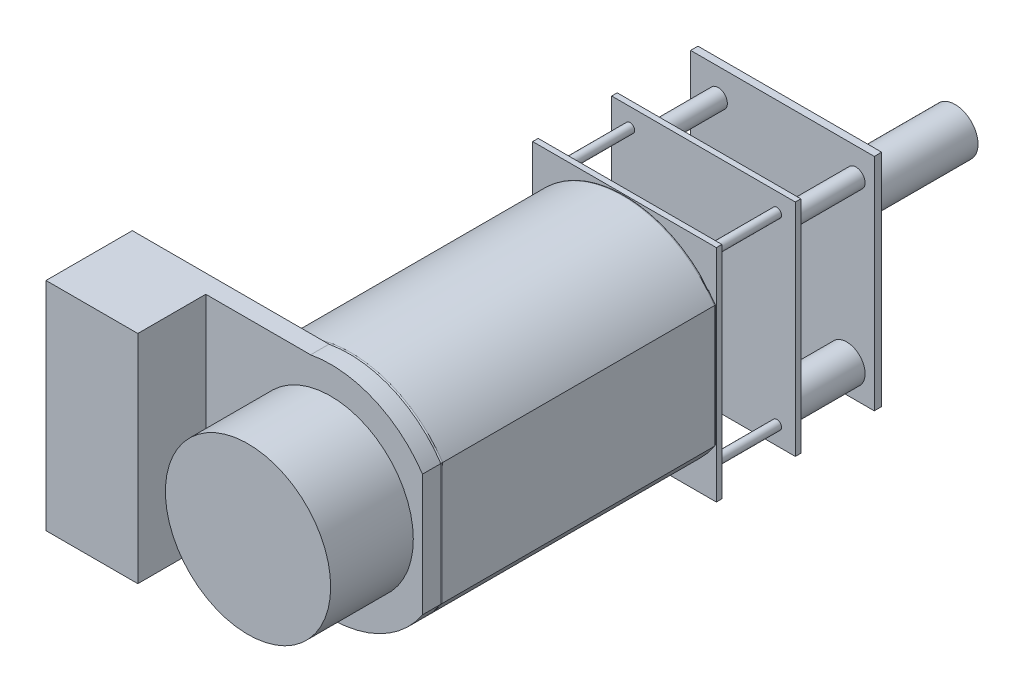
SolidWorks part; units mm, degrees
ref_plane "Front Plane" through (0, 0, 0) normal (0, 0, 1) x (1, 0, 0)
ref_plane "Top Plane" through (0, 0, 0) normal (0, 1, 0) x (1, 0, 0)
ref_plane "Right Plane" through (0, 0, 0) normal (1, 0, 0) x (0, 0, -1)
sketch "Sketch1" plane through (0, 0, 0) normal (0, 0, 1) x (1, 0, 0)
  line L2 (-5, -3.3166) -> (-5, 3.3166)
  line L4 (5, -3.3166) -> (5, 3.3166)
  line L5 (-3.8411, -4.6093) -> (3.8411, 4.6093) construction
  line L6 (-3.8411, 4.6093) -> (3.8411, -4.6093) construction
  arc A0 (-5, -3.3166) -> (5, -3.3166) centre (0, 0) ccw
  arc A1 (5, 3.3166) -> (-5, 3.3166) centre (0, 0) ccw
  point P0 (0, 0)
  dimension "D3" = 12
  dimension "D1" = 5
  dimension "D2" = 3.8411
extrude "Boss-Extrude1" add sketch "Sketch1" along normal blind 15
fillet "Fillet1" radius 0.1 8 edges at (0, -6, 15) (-5, 0, 15) (0, 6, 15) (5, 0, 15) (0, -6, 0) (5, 0, 0) (-5, 0, 0) (0, 6, 0)
sketch "Sketch2" plane through (0, 0, 15) normal (0, 0, 1) x (1, 0, 0)
  circle A0 centre (0, 0) radius 2.5
  dimension "D1" = 5
extrude "Boss-Extrude2" add sketch "Sketch2" along normal blind 1
sketch "Sketch3" plane through (0, 0, 16) normal (0, 0, 1) x (1, 0, 0)
  circle A0 centre (0, 0) radius 1.25
  dimension "D1" = 2.5
extrude "Boss-Extrude3" add sketch "Sketch3" along normal blind 0.1
sketch "Sketch4" plane through (0, 0, 0) normal (0, 0, -1) x (-1, 0, 0)
  line L1 (-5, -6) -> (5, -6)
  line L2 (-5, -6) -> (-5, 6)
  line L3 (-5, 6) -> (5, 6)
  line L4 (5, -6) -> (5, 6)
  line L5 (-5, -6) -> (5, 6) construction
  line L6 (-5, 6) -> (5, -6) construction
  point P0 (0, 0)
  dimension "D1" = 12
  dimension "D2" = 10
extrude "Boss-Extrude4" add sketch "Sketch4" along normal blind 0.3
sketch "Sketch5" plane through (0, 0, -0.3) normal (0, 0, -1) x (-1, 0, 0)
  circle A0 centre (0, 0) radius 0.5
  dimension "D1" = 1
extrude "Boss-Extrude5" add sketch "Sketch5" along normal blind 1
sketch "Sketch6" plane through (0, 0, -0.3) normal (0, 0, -1) x (-1, 0, 0)
  line L0 (-0.1, 1.4967) -> (0, 1.6699)
  line L1 (0, 1.6699) -> (0.1, 1.4967)
  line L2 (0.1688, 1.4905) -> (0.2982, 1.643)
  line L3 (0.2982, 1.643) -> (0.3656, 1.4548)
  line L4 (0.4323, 1.4364) -> (0.5867, 1.5634)
  line L5 (0.5867, 1.5634) -> (0.6195, 1.3661)
  line L6 (0.6818, 1.3361) -> (0.8565, 1.4335)
  line L7 (0.8565, 1.4335) -> (0.8535, 1.2335)
  line L8 (0.9094, 1.1929) -> (1.0987, 1.2575)
  line L9 (1.0987, 1.2575) -> (1.06, 1.0613)
  line L10 (1.1078, 1.0113) -> (1.3056, 1.0411)
  line L11 (1.3056, 1.0411) -> (1.2325, 0.855)
  line L12 (1.2706, 0.7973) -> (1.4705, 0.7913)
  line L13 (1.4705, 0.7913) -> (1.3653, 0.6212)
  line L14 (1.3925, 0.5576) -> (1.5881, 0.516)
  line L15 (1.5881, 0.516) -> (1.4543, 0.3674)
  line L16 (1.4697, 0.3) -> (1.6548, 0.2242)
  line L17 (1.6548, 0.2242) -> (1.4965, 0.1018)
  line L18 (1.4996, 0.0328) -> (1.6682, -0.0749)
  line L19 (1.6682, -0.0749) -> (1.4907, -0.167)
  line L20 (1.4814, -0.2355) -> (1.628, -0.3716)
  line L21 (1.628, -0.3716) -> (1.4369, -0.4305)
  line L22 (1.4155, -0.4963) -> (1.5355, -0.6563)
  line L23 (1.5355, -0.6563) -> (1.3369, -0.6802)
  line L24 (1.3042, -0.741) -> (1.3936, -0.9199)
  line L25 (1.3936, -0.9199) -> (1.194, -0.908)
  line L26 (1.1509, -0.962) -> (1.207, -1.154)
  line L27 (1.207, -1.154) -> (1.0127, -1.1066)
  line L28 (0.9606, -1.152) -> (0.9815, -1.351)
  line L29 (0.9815, -1.351) -> (0.7988, -1.2696)
  line L30 (0.7395, -1.3051) -> (0.7245, -1.5045)
  line L31 (0.7245, -1.5045) -> (0.5593, -1.3918)
  line L32 (0.4946, -1.4161) -> (0.4442, -1.6097)
  line L33 (0.4442, -1.6097) -> (0.3018, -1.4693)
  line L34 (0.2338, -1.4817) -> (0.1497, -1.6631)
  line L35 (0.1497, -1.6631) -> (0.0346, -1.4996)
  line L36 (-0.0346, -1.4996) -> (-0.1497, -1.6631)
  line L37 (-0.1497, -1.6631) -> (-0.2338, -1.4817)
  line L38 (-0.3018, -1.4693) -> (-0.4442, -1.6097)
  line L39 (-0.4442, -1.6097) -> (-0.4946, -1.4161)
  line L40 (-0.5593, -1.3918) -> (-0.7245, -1.5045)
  line L41 (-0.7245, -1.5045) -> (-0.7395, -1.3051)
  line L42 (-0.7988, -1.2696) -> (-0.9815, -1.351)
  line L43 (-0.9815, -1.351) -> (-0.9606, -1.152)
  line L44 (-1.0127, -1.1066) -> (-1.207, -1.154)
  line L45 (-1.207, -1.154) -> (-1.1509, -0.962)
  line L46 (-1.194, -0.908) -> (-1.3936, -0.9199)
  line L47 (-1.3936, -0.9199) -> (-1.3042, -0.741)
  line L48 (-1.3369, -0.6802) -> (-1.5355, -0.6563)
  line L49 (-1.5355, -0.6563) -> (-1.4155, -0.4963)
  line L50 (-1.4369, -0.4305) -> (-1.628, -0.3716)
  line L51 (-1.628, -0.3716) -> (-1.4814, -0.2355)
  line L52 (-1.4907, -0.167) -> (-1.6682, -0.0749)
  line L53 (-1.6682, -0.0749) -> (-1.4996, 0.0328)
  line L54 (-1.4965, 0.1018) -> (-1.6548, 0.2242)
  line L55 (-1.6548, 0.2242) -> (-1.4697, 0.3)
  line L56 (-1.4543, 0.3674) -> (-1.5881, 0.516)
  line L57 (-1.5881, 0.516) -> (-1.3925, 0.5576)
  line L58 (-1.3653, 0.6212) -> (-1.4705, 0.7913)
  line L59 (-1.4705, 0.7913) -> (-1.2706, 0.7973)
  line L60 (-1.2325, 0.855) -> (-1.3056, 1.0411)
  line L61 (-1.3056, 1.0411) -> (-1.1078, 1.0113)
  line L62 (-1.06, 1.0613) -> (-1.0987, 1.2575)
  line L63 (-1.0987, 1.2575) -> (-0.9094, 1.1929)
  line L64 (-0.8535, 1.2335) -> (-0.8565, 1.4335)
  line L65 (-0.8565, 1.4335) -> (-0.6818, 1.3361)
  line L66 (-0.6195, 1.3661) -> (-0.5867, 1.5634)
  line L67 (-0.5867, 1.5634) -> (-0.4323, 1.4364)
  line L68 (-0.3656, 1.4548) -> (-0.2982, 1.643)
  line L69 (-0.2982, 1.643) -> (-0.1688, 1.4905)
  circle A0 centre (0, 0) radius 0.5
  arc A1 (-1.06, 1.0613) -> (-1.1078, 1.0113) centre (0, 0) ccw
  arc A2 (-0.8535, 1.2335) -> (-0.9094, 1.1929) centre (0, 0) ccw
  arc A3 (-0.6195, 1.3661) -> (-0.6818, 1.3361) centre (0, 0) ccw
  arc A4 (-0.3656, 1.4548) -> (-0.4323, 1.4364) centre (0, 0) ccw
  arc A5 (-0.1, 1.4967) -> (-0.1688, 1.4905) centre (0, 0) ccw
  arc A6 (0.1688, 1.4905) -> (0.1, 1.4967) centre (0, 0) ccw
  arc A7 (0.4323, 1.4364) -> (0.3656, 1.4548) centre (0, 0) ccw
  arc A8 (0.6818, 1.3361) -> (0.6195, 1.3661) centre (0, 0) ccw
  arc A9 (0.9094, 1.1929) -> (0.8535, 1.2335) centre (0, 0) ccw
  arc A10 (1.1078, 1.0113) -> (1.06, 1.0613) centre (0, 0) ccw
  arc A11 (1.2706, 0.7973) -> (1.2325, 0.855) centre (0, 0) ccw
  arc A12 (1.3925, 0.5576) -> (1.3653, 0.6212) centre (0, 0) ccw
  arc A13 (1.4697, 0.3) -> (1.4543, 0.3674) centre (0, 0) ccw
  arc A14 (1.4996, 0.0328) -> (1.4965, 0.1018) centre (0, 0) ccw
  arc A15 (1.4814, -0.2355) -> (1.4907, -0.167) centre (0, 0) ccw
  arc A16 (1.4155, -0.4963) -> (1.4369, -0.4305) centre (0, 0) ccw
  arc A17 (1.3042, -0.741) -> (1.3369, -0.6802) centre (0, 0) ccw
  arc A18 (1.1509, -0.962) -> (1.194, -0.908) centre (0, 0) ccw
  arc A19 (0.9606, -1.152) -> (1.0127, -1.1066) centre (0, 0) ccw
  arc A20 (0.7395, -1.3051) -> (0.7988, -1.2696) centre (0, 0) ccw
  arc A21 (0.4946, -1.4161) -> (0.5593, -1.3918) centre (0, 0) ccw
  arc A22 (0.2338, -1.4817) -> (0.3018, -1.4693) centre (0, 0) ccw
  arc A23 (-0.0346, -1.4996) -> (0.0346, -1.4996) centre (0, 0) ccw
  arc A24 (-0.3018, -1.4693) -> (-0.2338, -1.4817) centre (0, 0) ccw
  arc A25 (-0.5593, -1.3918) -> (-0.4946, -1.4161) centre (0, 0) ccw
  arc A26 (-0.7988, -1.2696) -> (-0.7395, -1.3051) centre (0, 0) ccw
  arc A27 (-1.0127, -1.1066) -> (-0.9606, -1.152) centre (0, 0) ccw
  arc A28 (-1.194, -0.908) -> (-1.1509, -0.962) centre (0, 0) ccw
  arc A29 (-1.3369, -0.6802) -> (-1.3042, -0.741) centre (0, 0) ccw
  arc A30 (-1.4369, -0.4305) -> (-1.4155, -0.4963) centre (0, 0) ccw
  arc A31 (-1.4907, -0.167) -> (-1.4814, -0.2355) centre (0, 0) ccw
  arc A32 (-1.4965, 0.1018) -> (-1.4996, 0.0328) centre (0, 0) ccw
  arc A33 (-1.4543, 0.3674) -> (-1.4697, 0.3) centre (0, 0) ccw
  arc A34 (-1.3653, 0.6212) -> (-1.3925, 0.5576) centre (0, 0) ccw
  arc A35 (-1.2325, 0.855) -> (-1.2706, 0.7973) centre (0, 0) ccw
  point P112 (0, 0)
  dimension "D1" = 1
  dimension "D2" = 3
  dimension "D3" = 0.2
  dimension "D4" = 0.2
  dimension "D5" = 60
  dimension "D6" = 35
extrude "Boss-Extrude6" add sketch "Sketch6" along normal blind 0.5
sketch "Sketch8" plane through (0, 0, -0.3) normal (0, 0, -1) x (-1, 0, 0)
  line L0 (5, -6) -> (5, 6) construction
  line L1 (-5, -6) -> (5, -6) construction
  line L2 (-5, 6) -> (-5, -6) construction
  circle A0 centre (-4, 5) radius 0.25
  circle A1 centre (4, 5) radius 0.25
  circle A2 centre (4, -5) radius 0.25
  circle A3 centre (-4, -5) radius 0.25
  dimension "D4" = 0.5
  dimension "D1" = 10
  dimension "D2" = 1
  dimension "D3" = 1
  dimension "D5" = 1
extrude "Boss-Extrude7" add sketch "Sketch8" along normal blind 4
sketch "Sketch9" plane through (0, 0, -4.3) normal (0, 0, -1) x (-1, 0, 0)
  line L1 (-5, -6) -> (5, -6)
  line L2 (-5, -6) -> (-5, 6)
  line L3 (-5, 6) -> (5, 6)
  line L4 (5, -6) -> (5, 6)
  line L5 (-5, -6) -> (5, 6) construction
  line L6 (-5, 6) -> (5, -6) construction
  point P0 (0, 0)
extrude "Boss-Extrude8" add sketch "Sketch9" along normal blind 0.3
sketch "Sketch10" plane through (0, 0, -4.6) normal (0, 0, -1) x (-1, 0, 0)
  line L0 (5, 6) -> (-5, 6) construction
  line L1 (-5, 6) -> (-5, -6) construction
  line L2 (-5, -6) -> (5, -6) construction
  line L3 (5, -6) -> (5, 6) construction
  circle A0 centre (-4, 4.5) radius 0.5
  circle A1 centre (-3.5, -4.5) radius 1
  circle A2 centre (3.5, 4.5) radius 0.5
  dimension "D5" = 2
  dimension "D6" = 1
  dimension "D7" = 1
  dimension "D8" = 1.5
  dimension "D1" = 1.5
  dimension "D2" = 1
  dimension "D3" = 1.5
  dimension "D4" = 1.5
extrude "Boss-Extrude9" add sketch "Sketch10" along normal blind 4
sketch "Sketch11" plane through (0, 0, -8.6) normal (0, 0, -1) x (-1, 0, 0)
  line L1 (-5, -6) -> (5, -6)
  line L2 (-5, -6) -> (-5, 6)
  line L3 (-5, 6) -> (5, 6)
  line L4 (5, -6) -> (5, 6)
  line L5 (-5, -6) -> (5, 6) construction
  line L6 (-5, 6) -> (5, -6) construction
  point P0 (0, 0)
extrude "Boss-Extrude10" add sketch "Sketch11" along normal blind 0.4
sketch "Sketch14" plane through (0, 0, -9) normal (0, 0, -1) x (-1, 0, 0)
  circle A0 centre (0, 0) radius 1.25
  dimension "D1" = 2.5
extrude "Boss-Extrude11" add sketch "Sketch14" along normal blind 9
sketch "Sketch15" plane through (0, 0, -9) normal (0, 0, -1) x (-1, 0, 0)
  circle A0 centre (0, 0) radius 1.5
  dimension "D1" = 3
extrude "Boss-Extrude12" add sketch "Sketch15" along normal blind 0.8
sketch "Sketch16" plane through (0, 0, 15) normal (0, 0, 1) x (1, 0, 0)
  line L0 (-4.9, 3.2863) -> (-4.9, -3.2863) construction
  line L4 (5, -3.3166) -> (5, 3.3166)
  line L5 (-3.8411, -4.6093) -> (3.8411, 4.6093) construction
  line L6 (-3.8411, 4.6093) -> (3.8411, -4.6093) construction
  line L8 (-1.0909, -5.9) -> (-11.8, -5.9)
  line L10 (-1.0909, 5.9) -> (-11.8, 5.9)
  line L11 (-11.8, -5.9) -> (-11.8, 5.9)
  arc A0 (-1.0909, -5.9) -> (5, -3.3166) centre (0, 0) ccw
  arc A1 (5, 3.3166) -> (-1.0909, 5.9) centre (0, 0) ccw
  point P0 (0, 0)
  dimension "D1" = 12
  dimension "D2" = 1.0589
  dimension "D3" = 9.9
  dimension "D4" = 6.8
  dimension "D5" = 11.8
  dimension "D6" = 1.0909
extrude "Boss-Extrude13" add sketch "Sketch16" along normal blind 1
sketch "Sketch17" plane through (0, 0, 16) normal (0, 0, 1) x (1, 0, 0)
  circle A0 centre (0, 0) radius 4.5
  dimension "D1" = 9
extrude "Boss-Extrude14" add sketch "Sketch17" along normal blind 4.5
sketch "Sketch18" plane through (0, 0, 16) normal (0, 0, 1) x (1, 0, 0)
  line L0 (-11.8, -5.9) -> (-1.0909, -5.9) construction
  line L1 (-11.8, 5.9) -> (-6.8, 5.9)
  line L2 (-11.8, 5.9) -> (-11.8, -5.9)
  line L3 (-11.8, -5.9) -> (-6.8, -5.9)
  line L4 (-6.8, 5.9) -> (-6.8, -5.9)
  dimension "D1" = 5
extrude "Boss-Extrude15" add sketch "Sketch18" along normal blind 3.7
sketch "Sketch19" plane through (-11.8, 0, 0) normal (-1, 0, 0) x (0, 0, 1)
  line L0 (19.7, 5.9) -> (15, 5.9) construction
  line L1 (19.6, 5.8) -> (15.5, 5.8)
  line L2 (19.6, 5.8) -> (19.6, -5.8)
  line L3 (19.6, -5.8) -> (15.5, -5.8)
  line L4 (15.5, 5.8) -> (15.5, -5.8)
  line L5 (19.7, -5.9) -> (15, -5.9) construction
  line L6 (19.7, 5.9) -> (19.7, -5.9) construction
  line L7 (15, 5.9) -> (15, -5.9) construction
  dimension "D1" = 0.1
  dimension "D2" = 0.1
  dimension "D3" = 0.1
  dimension "D4" = 0.5
extrude "Cut-Extrude1" cut sketch "Sketch19" against normal blind 3.2
